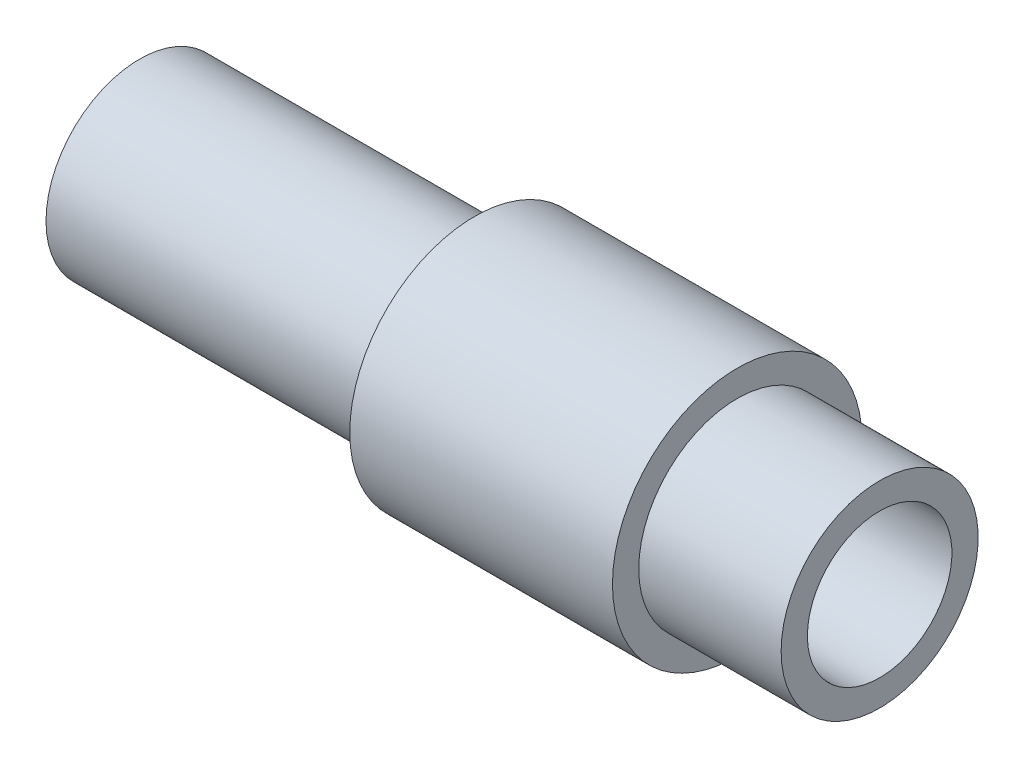
SolidWorks part; units mm, degrees
ref_plane "Front Plane" through (0, 0, 0) normal (0, 0, 1) x (1, 0, 0)
ref_plane "Top Plane" through (0, 0, 0) normal (0, 1, 0) x (1, 0, 0)
ref_plane "Right Plane" through (0, 0, 0) normal (1, 0, 0) x (0, 0, -1)
sketch "Sketch1" plane through (0, 0, 0) normal (0, 0, 1) x (1, 0, 0)
  line L0 (-83.6737, 19.6329) -> (88.7001, 19.6329) construction
  line L1 (-72.1427, 24.7579) -> (-44.6427, 24.7579)
  line L2 (-72.1427, 26.7579) -> (-46.6427, 26.7579)
  line L3 (-46.6427, 26.7579) -> (-46.6427, 29.1329)
  line L4 (-46.6427, 29.1329) -> (-26.6427, 29.1329)
  line L5 (-44.6427, 24.7579) -> (-44.6427, 27.1329)
  line L7 (-72.1427, 26.7579) -> (-72.1427, 24.7579)
  line L9 (-44.6427, 27.1329) -> (-26.6427, 27.1329) construction
  line L10 (-26.6427, 29.1329) -> (-26.6427, 27.1329)
  line L11 (-26.6427, 27.1329) -> (-15.8035, 27.1329)
  line L18 (-28.6427, 27.1329) -> (-28.6427, 25.1329)
  line L19 (-28.6427, 25.1329) -> (-15.8035, 25.1329)
  line L21 (-15.8035, 27.1329) -> (-15.8035, 25.1329)
  line L22 (-42.6427, 27.1329) -> (-28.6427, 27.1329) construction
  line L23 (-42.6427, 27.1329) -> (-42.6427, 27.1329) construction
  line L24 (-42.6427, 27.1329) -> (-42.6427, 27.1329) construction
  line L25 (-42.6427, 27.1329) -> (-42.6427, 27.1329) construction
  line L26 (-42.6427, 27.1329) -> (-42.6427, 27.1329) construction
  line L27 (-42.6427, 27.1329) -> (-42.6427, 27.1329) construction
  line L28 (-44.6427, 27.1329) -> (-28.6427, 27.1329)
  dimension "D2" = 14.25
  dimension "D3" = 25.5
  dimension "D4" = 20
  dimension "D5" = 19
  dimension "D7" = 15
  dimension "D8" = 10.8392
  dimension "D1" = 2
  dimension "D6" = 2
revolve "Revolve1" add sketch "Sketch1" angle 360 about L0
